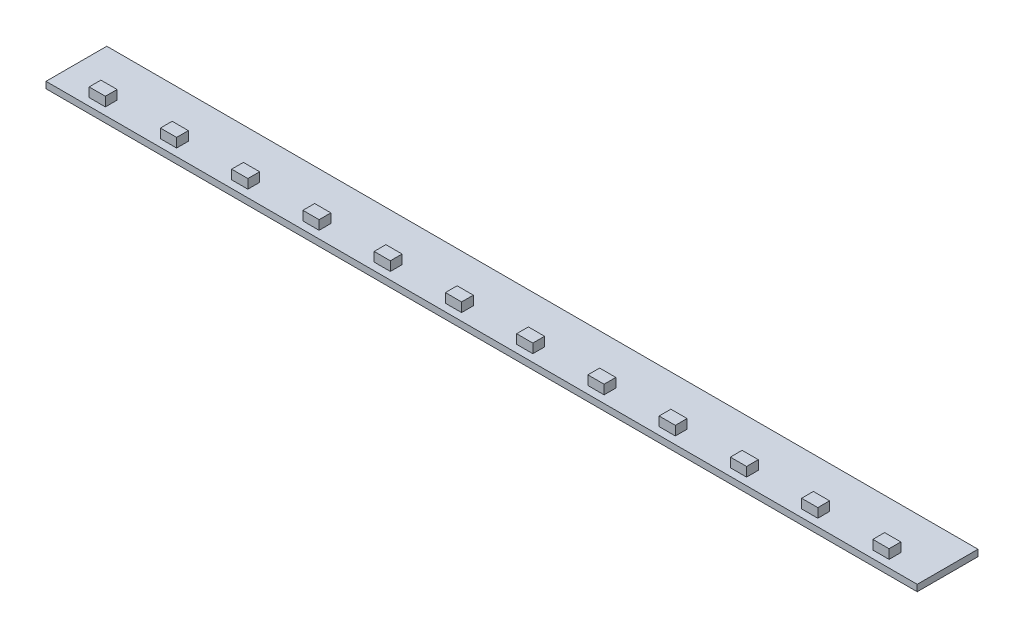
SolidWorks part; units mm, degrees
ref_plane "Front Plane" through (0, 0, 0) normal (0, 0, 1) x (1, 0, 0)
ref_plane "Top Plane" through (0, 0, 0) normal (0, 1, 0) x (1, 0, 0)
ref_plane "Right Plane" through (0, 0, 0) normal (1, 0, 0) x (0, 0, -1)
sketch "Sketch2" plane through (0, 0, 0) normal (0, 1, 0) x (1, 0, 0)
  line L0 (-107.5, 7.5) -> (107.5, 7.5)
  line L1 (107.5, 7.5) -> (107.5, -7.5)
  line L4 (107.5, -7.5) -> (-107.5, -7.5)
  line L7 (-107.5, -7.5) -> (-107.5, 7.5)
  point P2 (0, 7.5)
  point P4 (0, 0)
  point P10 (0, -7.5)
  point P11 (-107.5, 0)
  point P12 (107.5, 0)
  dimension "D1" = 215
  dimension "D2" = 15
extrude "Boss-Extrude1" add sketch "Sketch2" along normal blind 1.6
sketch "Sketch4" plane through (0, 1.6, 0) normal (0, 1, 0) x (1, 0, 0)
  line L1 (-98.7, -2.75) -> (-94.7, -2.75)
  line L2 (-98.7, -2.75) -> (-98.7, -5.65)
  line L3 (-98.7, -5.65) -> (-94.7, -5.65)
  line L4 (-94.7, -2.75) -> (-94.7, -5.65)
  line L5 (-98.7, -2.75) -> (-94.7, -5.65) construction
  line L6 (-98.7, -5.65) -> (-94.7, -2.75) construction
  line L8 (-107.5, 7.5) -> (-107.5, -7.5) construction
  line L9 (107.5, 7.5) -> (-107.5, 7.5) construction
  line L10 (-81.118, -2.75) -> (-77.118, -2.75)
  line L11 (-81.118, -2.75) -> (-81.118, -5.65)
  line L12 (-81.118, -5.65) -> (-77.118, -5.65)
  line L13 (-77.118, -2.75) -> (-77.118, -5.65)
  line L14 (-81.118, -2.75) -> (-77.118, -5.65) construction
  line L15 (-81.118, -5.65) -> (-77.118, -2.75) construction
  line L16 (-63.536, -2.75) -> (-59.536, -2.75)
  line L17 (-63.536, -2.75) -> (-63.536, -5.65)
  line L18 (-63.536, -5.65) -> (-59.536, -5.65)
  line L19 (-59.536, -2.75) -> (-59.536, -5.65)
  line L20 (-63.536, -2.75) -> (-59.536, -5.65) construction
  line L21 (-63.536, -5.65) -> (-59.536, -2.75) construction
  line L22 (-45.955, -2.75) -> (-41.955, -2.75)
  line L23 (-45.955, -2.75) -> (-45.955, -5.65)
  line L24 (-45.955, -5.65) -> (-41.955, -5.65)
  line L25 (-41.955, -2.75) -> (-41.955, -5.65)
  line L26 (-45.955, -2.75) -> (-41.955, -5.65) construction
  line L27 (-45.955, -5.65) -> (-41.955, -2.75) construction
  line L28 (-28.373, -2.75) -> (-24.373, -2.75)
  line L29 (-28.373, -2.75) -> (-28.373, -5.65)
  line L30 (-28.373, -5.65) -> (-24.373, -5.65)
  line L31 (-24.373, -2.75) -> (-24.373, -5.65)
  line L32 (-28.373, -2.75) -> (-24.373, -5.65) construction
  line L33 (-28.373, -5.65) -> (-24.373, -2.75) construction
  line L34 (-10.791, -2.75) -> (-6.791, -2.75)
  line L35 (-10.791, -2.75) -> (-10.791, -5.65)
  line L36 (-10.791, -5.65) -> (-6.791, -5.65)
  line L37 (-6.791, -2.75) -> (-6.791, -5.65)
  line L38 (-10.791, -2.75) -> (-6.791, -5.65) construction
  line L39 (-10.791, -5.65) -> (-6.791, -2.75) construction
  line L40 (6.791, -2.75) -> (10.791, -2.75)
  line L41 (6.791, -2.75) -> (6.791, -5.65)
  line L42 (6.791, -5.65) -> (10.791, -5.65)
  line L43 (10.791, -2.75) -> (10.791, -5.65)
  line L44 (6.791, -2.75) -> (10.791, -5.65) construction
  line L45 (6.791, -5.65) -> (10.791, -2.75) construction
  line L46 (24.373, -2.75) -> (28.373, -2.75)
  line L47 (24.373, -2.75) -> (24.373, -5.65)
  line L48 (24.373, -5.65) -> (28.373, -5.65)
  line L49 (28.373, -2.75) -> (28.373, -5.65)
  line L50 (24.373, -2.75) -> (28.373, -5.65) construction
  line L51 (24.373, -5.65) -> (28.373, -2.75) construction
  line L52 (41.955, -2.75) -> (45.955, -2.75)
  line L53 (41.955, -2.75) -> (41.955, -5.65)
  line L54 (41.955, -5.65) -> (45.955, -5.65)
  line L55 (45.955, -2.75) -> (45.955, -5.65)
  line L56 (41.955, -2.75) -> (45.955, -5.65) construction
  line L57 (41.955, -5.65) -> (45.955, -2.75) construction
  line L58 (59.536, -2.75) -> (63.536, -2.75)
  line L59 (59.536, -2.75) -> (59.536, -5.65)
  line L60 (59.536, -5.65) -> (63.536, -5.65)
  line L61 (63.536, -2.75) -> (63.536, -5.65)
  line L62 (59.536, -2.75) -> (63.536, -5.65) construction
  line L63 (59.536, -5.65) -> (63.536, -2.75) construction
  line L64 (77.118, -2.75) -> (81.118, -2.75)
  line L65 (77.118, -2.75) -> (77.118, -5.65)
  line L66 (77.118, -5.65) -> (81.118, -5.65)
  line L67 (81.118, -2.75) -> (81.118, -5.65)
  line L68 (77.118, -2.75) -> (81.118, -5.65) construction
  line L69 (77.118, -5.65) -> (81.118, -2.75) construction
  line L70 (94.7, -2.75) -> (98.7, -2.75)
  line L71 (94.7, -2.75) -> (94.7, -5.65)
  line L72 (94.7, -5.65) -> (98.7, -5.65)
  line L73 (98.7, -2.75) -> (98.7, -5.65)
  line L74 (94.7, -2.75) -> (98.7, -5.65) construction
  line L75 (94.7, -5.65) -> (98.7, -2.75) construction
  point P0 (-96.7, -4.2)
  point P15 (-79.118, -4.2)
  point P21 (-61.536, -4.2)
  point P27 (-43.955, -4.2)
  point P33 (-26.373, -4.2)
  point P39 (-8.791, -4.2)
  point P45 (8.791, -4.2)
  point P51 (26.373, -4.2)
  point P57 (43.955, -4.2)
  point P63 (61.536, -4.2)
  point P69 (79.118, -4.2)
  point P75 (96.7, -4.2)
  dimension "D1" = 4
  dimension "D2" = 2.9
  dimension "D3" = 10.8
  dimension "D4" = 11.7
  dimension "D5" = 28.382
  dimension "D6" = 45.964
  dimension "D7" = 63.545
  dimension "D8" = 81.127
  dimension "D9" = 98.709
  dimension "D10" = 116.291
  dimension "D11" = 133.873
  dimension "D12" = 151.455
  dimension "D13" = 169.036
  dimension "D14" = 186.618
  dimension "D15" = 204.2
extrude "Boss-Extrude2" add sketch "Sketch4" along normal blind 2.28
